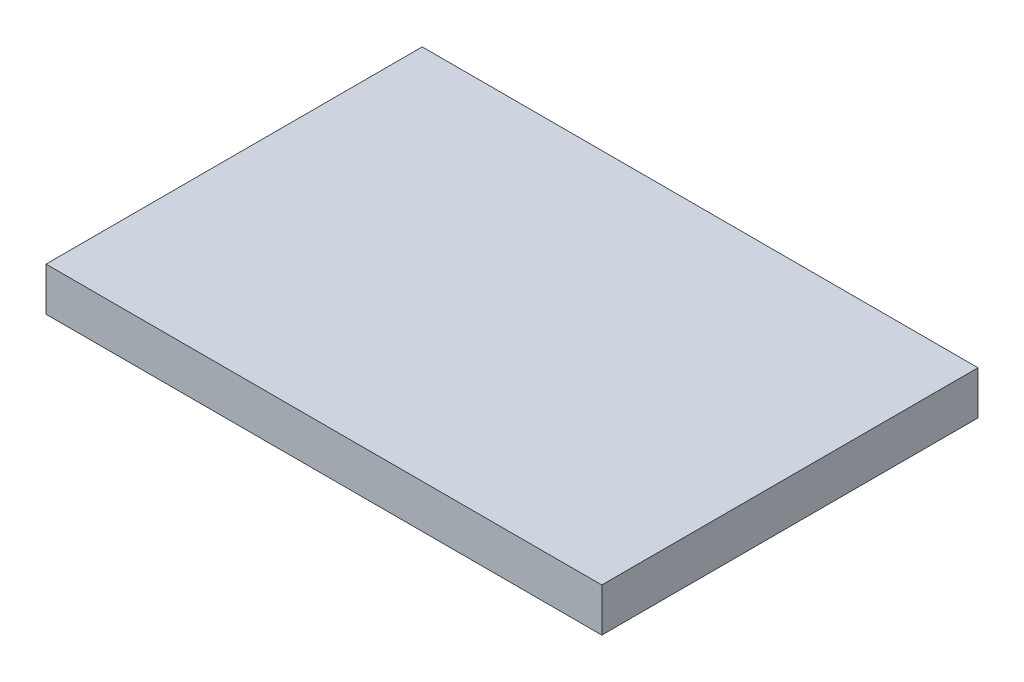
SolidWorks part; units mm, degrees
ref_plane "Front Plane" through (0, 0, 0) normal (0, 0, 1) x (1, 0, 0)
ref_plane "Top Plane" through (0, 0, 0) normal (0, 1, 0) x (1, 0, 0)
ref_plane "Right Plane" through (0, 0, 0) normal (1, 0, 0) x (0, 0, -1)
sketch "Sketch3" plane through (0, 0, 0) normal (0, 1, 0) x (1, 0, 0)
  line L1 (0, 0) -> (325, 0)
  line L2 (0, 0) -> (0, 220)
  line L3 (0, 220) -> (325, 220)
  line L4 (325, 0) -> (325, 220)
  dimension "D1" = 220
  dimension "D2" = 325
extrude "Boss-Extrude1" add sketch "Sketch3" along normal blind 25.4
